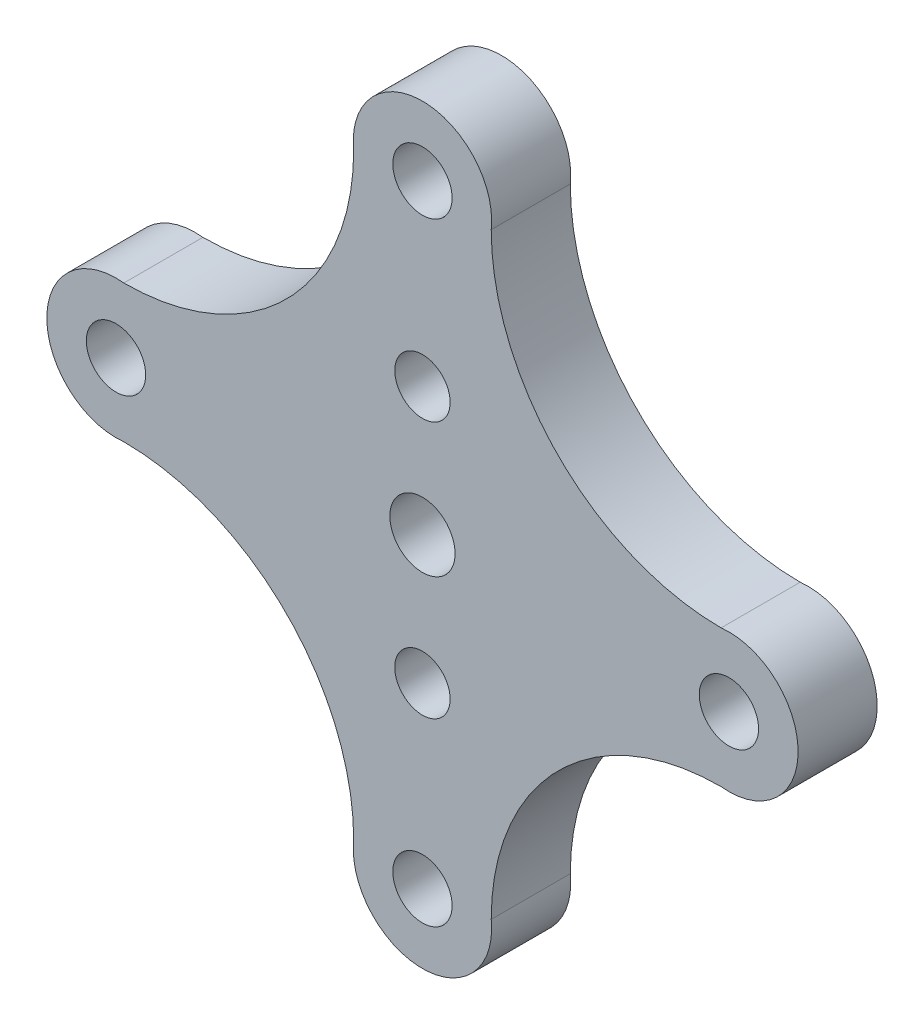
SolidWorks part; units mm, degrees
ref_plane "前视基准面" through (0, 0, 0) normal (0, 0, 1) x (1, 0, 0)
ref_plane "上视基准面" through (0, 0, 0) normal (0, 1, 0) x (1, 0, 0)
ref_plane "右视基准面" through (0, 0, 0) normal (1, 0, 0) x (0, 0, -1)
sketch "草图1" plane through (0, 0, 0) normal (0, 0, 1) x (1, 0, 0)
  circle A0 centre (0, 0) radius 1.65
  circle A1 centre (0, 0) radius 6.5 construction
  circle A2 centre (0, 0) radius 15.5 construction
  circle A3 centre (0, -6.5) radius 1.4
  circle A5 centre (0, 6.5) radius 1.4
  circle A6 centre (0, -15.5) radius 1.5
  circle A7 centre (-15.5, 0) radius 1.5
  circle A8 centre (0, 15.5) radius 1.5
  circle A9 centre (15.5, 0) radius 1.5
  circle A10 centre (0, 0) radius 32.5 construction
  circle A11 centre (0, -15.5) radius 3.5 construction
  arc A12 (-3.4776, -15.1048) -> (3.4776, -15.1048) centre (0, -15.5) ccw
  circle A13 centre (-15.5, 0) radius 3.5 construction
  arc A14 (-15.1048, 3.4776) -> (-15.1048, -3.4776) centre (-15.5, 0) ccw
  arc A15 (3.4776, 15.1048) -> (-3.4776, 15.1048) centre (0, 15.5) ccw
  arc A16 (15.1048, -3.4776) -> (15.1048, 3.4776) centre (15.5, 0) ccw
  arc A21 (-15.1048, 3.4776) -> (-3.4776, 15.1048) centre (-15.1048, 15.1048) ccw
  arc A22 (3.4776, 15.1048) -> (15.1048, 3.4776) centre (15.1048, 15.1048) ccw
  arc A23 (15.1048, -3.4776) -> (3.4776, -15.1048) centre (15.1048, -15.1048) ccw
  arc A24 (-15.1048, -3.4776) -> (-3.4776, -15.1048) centre (-15.1048, -15.1048) cw
  dimension "D1" = 3.3
  dimension "D2" = 13
  dimension "D3" = 31
  dimension "D4" = 2.8
  dimension "D6" = 3
  dimension "D8" = 65
  dimension "D9" = 7
  dimension "D10" = 7
  dimension "D5" = 2
  dimension "D7" = 4
  dimension "D11" = 4
extrude "凸台-拉伸1" add sketch "草图1" along normal blind 4 contours A10
